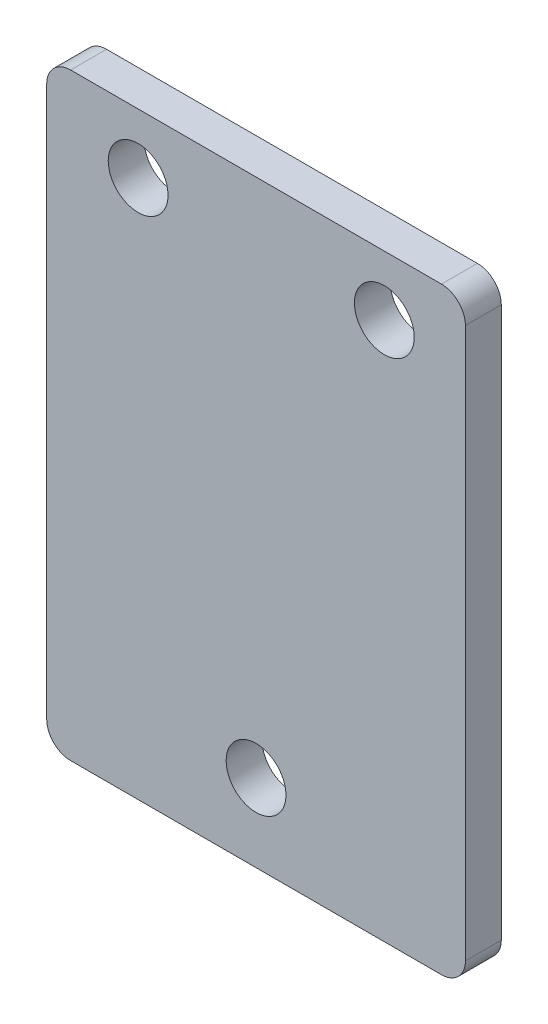
SolidWorks part; units mm, degrees
material "6061-T6 (SS)"
ref_plane "Front Plane" through (0, 0, 0) normal (0, 0, 1) x (1, 0, 0)
ref_plane "Top Plane" through (0, 0, 0) normal (0, 1, 0) x (1, 0, 0)
ref_plane "Right Plane" through (0, 0, 0) normal (1, 0, 0) x (0, 0, -1)
sketch "Sketch1" plane through (0, 0, 0) normal (0, 0, -1) x (1, 0, 0)
  line L0 (0, 0) -> (-33.1489, 0) construction
  line L1 (-15.5, 35) -> (15.5, 35)
  line L2 (-17.5, 33) -> (-17.5, -13)
  line L3 (-15.5, -15) -> (15.5, -15)
  line L4 (17.5, 33) -> (17.5, -13)
  circle A0 centre (0, 28.5) radius 2.5
  circle A1 centre (-9.8588, -10) radius 2.5
  circle A2 centre (10.7208, -10) radius 2.5
  arc A3 (17.5, 33) -> (15.5, 35) centre (15.5, 33) ccw
  arc A4 (15.5, -15) -> (17.5, -13) centre (15.5, -13) ccw
  arc A5 (-15.5, -15) -> (-17.5, -13) centre (-15.5, -13) cw
  arc A6 (-17.5, 33) -> (-15.5, 35) centre (-15.5, 33) cw
  point P14 (17.5, 35)
  point P19 (-17.5, -15)
  point P22 (-17.5, 35)
  dimension "D2" = 50
  dimension "D3" = 17.5
  dimension "D5" = 5
  dimension "D7" = 10
  dimension "D10" = 28.5
  dimension "D4" = 5
  dimension "D8" = 5
  dimension "D6" = 5
  dimension "D11" = 2
  dimension "D1" = 35
  dimension "D9" = 10
extrude "Boss-Extrude1" add sketch "Sketch1" along normal blind 3
